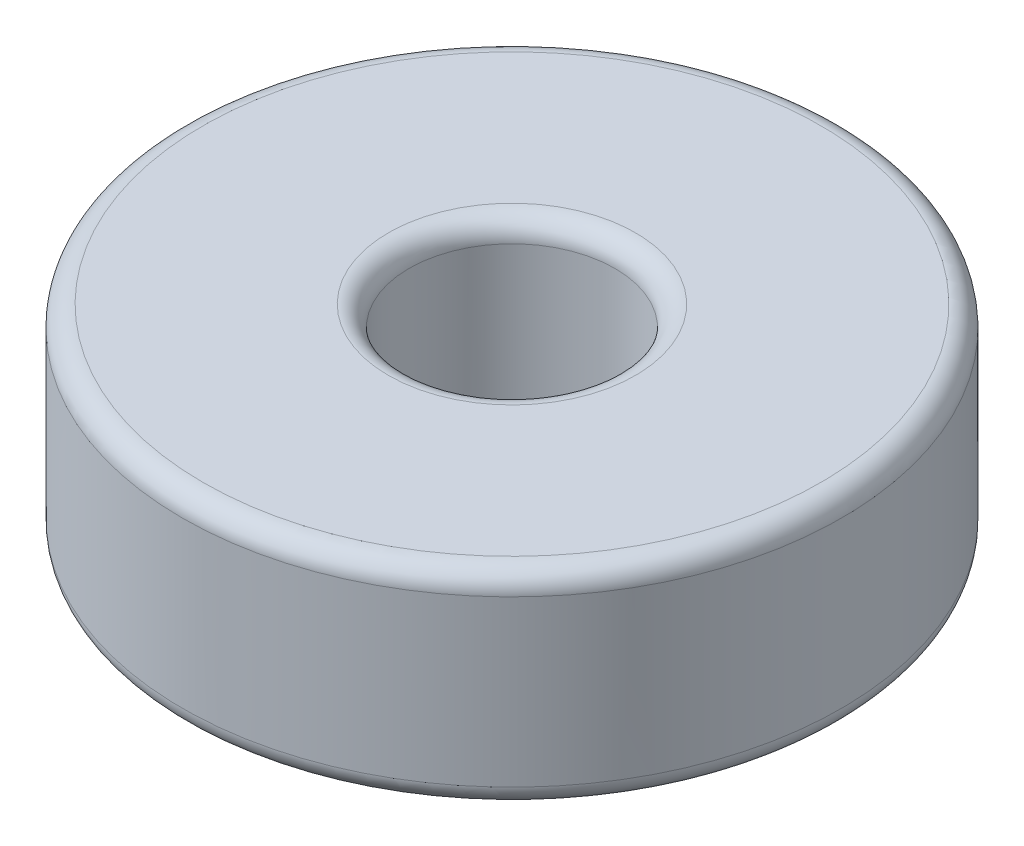
SolidWorks part; units mm, degrees
ref_plane "Plan de face" through (0, 0, 0) normal (0, 0, 1) x (1, 0, 0)
ref_plane "Plan de dessus" through (0, 0, 0) normal (0, 1, 0) x (1, 0, 0)
ref_plane "Plan de droite" through (0, 0, 0) normal (1, 0, 0) x (0, 0, -1)
sketch "Esquisse1" plane through (0, 0, 0) normal (0, 0, 1) x (1, 0, 0)
  line L0 (2.5, 0) -> (2.5, 5)
  line L1 (2.5, 5) -> (8, 5)
  line L2 (8, 5) -> (8, 0)
  line L3 (8, 0) -> (2.5, 0)
  line L4 (0, 0) -> (0, 5) construction
  dimension "D1" = 5
  dimension "D2" = 16
  dimension "D3" = 5
revolve "Révolution1" add sketch "Esquisse1" angle 360 about L4
fillet "Congé1" radius 0.5 4 edges at (0, 0, -2.5) (0, 0, -8) (0, 5, -8) (0, 5, -2.5)
